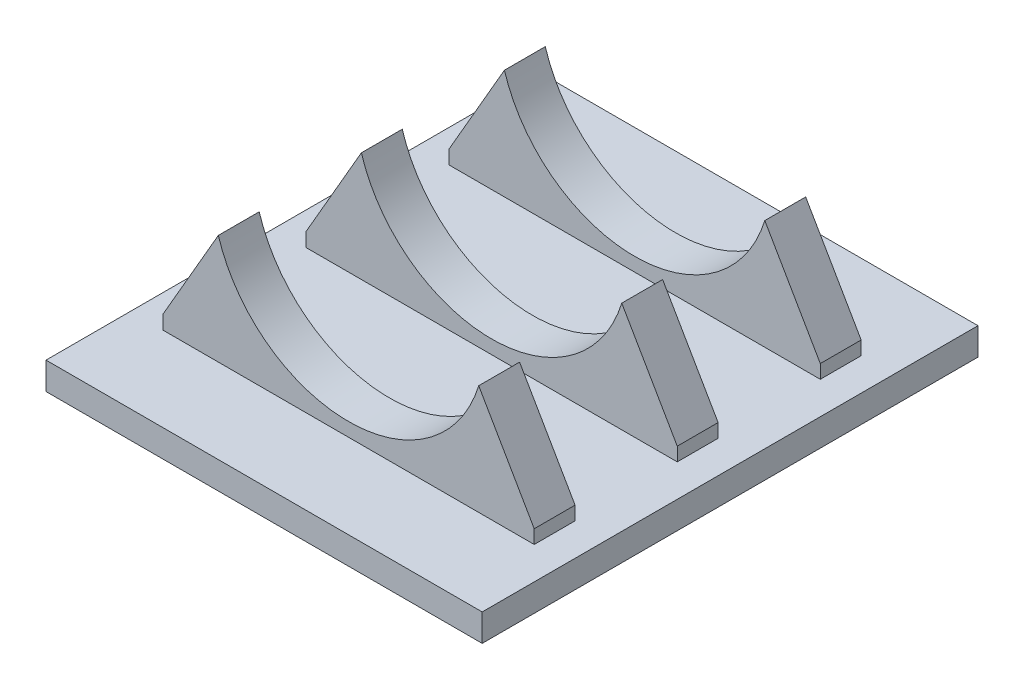
SolidWorks part; units mm, degrees
ref_plane "前视基准面" through (0, 0, 0) normal (0, 0, 1) x (1, 0, 0)
ref_plane "上视基准面" through (0, 0, 0) normal (0, 1, 0) x (1, 0, 0)
ref_plane "右视基准面" through (0, 0, 0) normal (1, 0, 0) x (0, 0, -1)
sketch "草图1" plane through (0, 0, 0) normal (0, 0, 1) x (1, 0, 0)
  line L0 (0, 0) -> (0, 64.4086) construction
  line L1 (0, 0) -> (-68.1529, 0) construction
  line L2 (-47.7841, 35.2798) -> (-68.1529, 0)
  line L7 (47.7841, 35.2798) -> (68.1529, 0)
  line L8 (-2.5615, -10) -> (2.5615, -10)
  line L9 (-68.1529, 0) -> (-68.1529, -5)
  line L10 (-68.1529, -5) -> (68.1529, -5)
  line L11 (68.1529, -5) -> (68.1529, 0)
  arc A0 (47.7841, 35.2798) -> (-47.7841, 35.2798) centre (0, 50) cw
  dimension "D1" = 5
  dimension "D2" = 60
  dimension "D3" = 136.3057
extrude "凸台-拉伸1" add sketch "草图1" along normal blind 15 contours A0 L2 L9 L10 L11 L7
pattern_linear "阵列(线性)1" count 3 spacing 52.5 along (0, 0, 1) of bodies 106
sketch "草图2" plane through (0, -5, 0) normal (0, -1, 0) x (-1, 0, 0)
  line L0 (68.1529, -60) -> (-68.1529, -60) construction
  line L1 (68.1529, -67.5) -> (68.1529, -52.5) construction
  line L2 (-68.1529, -67.5) -> (-68.1529, -52.5) construction
  line L3 (0, -60) -> (0, -193.8743) construction
  line L4 (-80.0459, -150.989) -> (-80.0459, 30.989)
  line L5 (80.0459, -150.989) -> (80.0459, 30.989)
  line L6 (-80.0459, -150.989) -> (80.0459, -150.989)
  line L7 (-80.0459, 30.989) -> (80.0459, 30.989)
  point P12 (0, -150.989)
  point P15 (80.0459, -60)
  point P16 (-80.0459, -60)
  dimension "D1" = 181.978
extrude "凸台-拉伸2" add sketch "草图2" along normal blind 10 contours L6 L5 L7 L4
